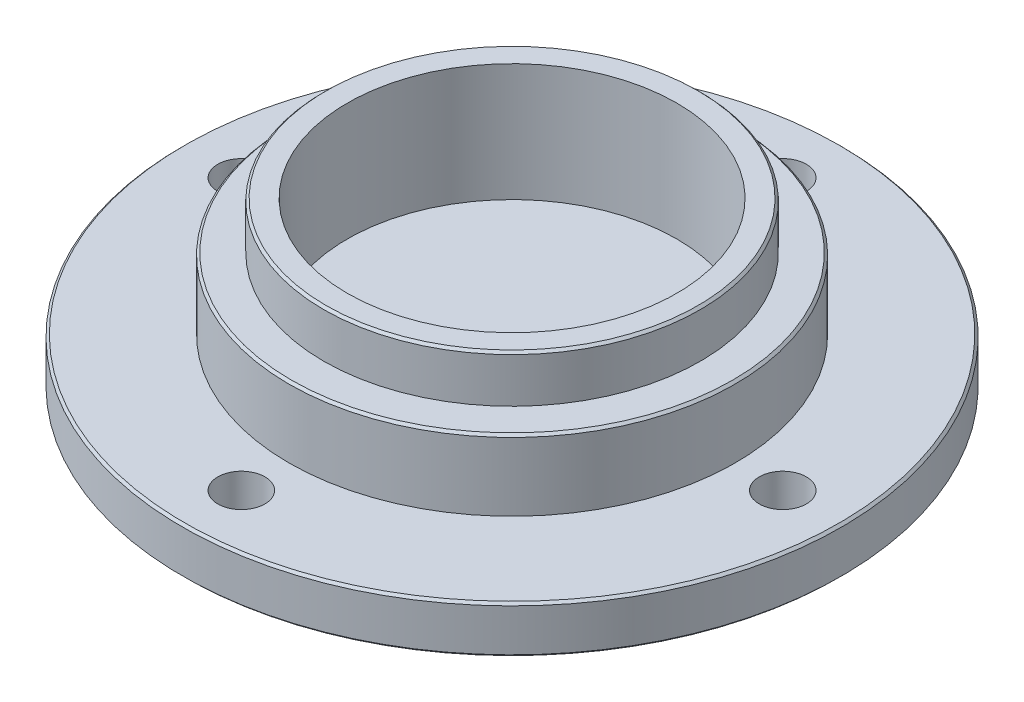
SolidWorks part; units mm, degrees
ref_plane "前视基准面" through (0, 0, 0) normal (0, 0, 1) x (1, 0, 0)
ref_plane "上视基准面" through (0, 0, 0) normal (0, 1, 0) x (1, 0, 0)
ref_plane "右视基准面" through (0, 0, 0) normal (1, 0, 0) x (0, 0, -1)
other "Configuration Table"
sketch "草图1" plane through (0, 0, 0) normal (0, 1, 0) x (1, 0, 0)
  circle A0 centre (0, 0) radius 47.4
  dimension "D1" = 94.8
extrude "凸台-拉伸1" add sketch "草图1" along normal blind 15
sketch "草图2" plane through (0, 15, 0) normal (0, 1, 0) x (1, 0, 0)
  circle A0 centre (0, 0) radius 40
  dimension "D1" = 80
extrude "凸台-拉伸2" add sketch "草图2" along normal blind 10
sketch "草图3" plane through (0, 0, 0) normal (0, -1, 0) x (1, 0, 0)
  circle A0 centre (0, 0) radius 70
  circle A1 centre (0, 0) radius 57.5 construction
  circle A2 centre (0, 57.5) radius 5
  circle A3 centre (57.5, 0) radius 5
  circle A4 centre (0, -57.5) radius 5
  circle A5 centre (-57.5, 0) radius 5
  point P15 (0, 0)
  dimension "D1" = 115
  dimension "D2" = 10
  dimension "D4" = 140
  dimension "D3" = 4
extrude "凸台-拉伸3" add sketch "草图3" along normal blind 10
sketch "草图4" plane through (0, 25, 0) normal (0, 1, 0) x (1, 0, 0)
  circle A0 centre (0, 0) radius 35
  dimension "D1" = 70
extrude "切除-拉伸1" cut sketch "草图4" against normal blind 25
chamfer "倒角1" distance 0.5 angle 45 4 edges at (0, 25, 40) (0, 15, 47.4) (0, 0, -70) (0, -10, -70)
